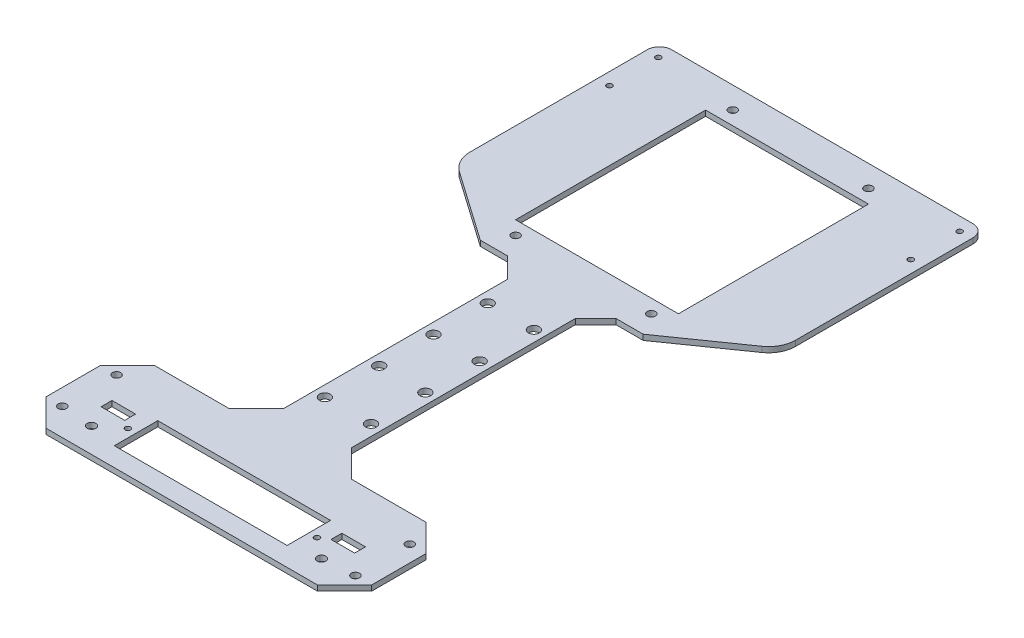
SolidWorks part; units mm, degrees
material "Acrílico (médio-alto impacto)"
ref_plane "Plano frontal" through (0, 0, 0) normal (0, 0, 1) x (1, 0, 0)
ref_plane "Plano superior" through (0, 0, 0) normal (0, 1, 0) x (1, 0, 0)
ref_plane "Plano direito" through (0, 0, 0) normal (1, 0, 0) x (0, 0, -1)
sketch "Esboço1" plane through (0, 0, 0) normal (0, 1, 0) x (1, 0, 0)
  line L0 (-18.0889, 17.9415) -> (-18.0889, 19.4415)
  line L1 (-13.5889, 23.9415) -> (97.4111, 23.9415)
  line L2 (-18.0889, 17.9415) -> (-18.0889, -45.8529)
  line L3 (-13.8247, -54.0444) -> (11.9111, -72.0648)
  line L4 (11.9111, -72.0648) -> (21.9111, -72.0648)
  line L5 (41.9111, -1077.9191) -> (41.9111, -72.0648) construction
  line L7 (97.6469, -54.0444) -> (71.9111, -72.0648)
  line L9 (101.9111, 17.9415) -> (101.9111, -45.8529)
  line L10 (101.9111, 17.9415) -> (101.9111, 19.4415)
  line L11 (21.9111, -72.0648) -> (29.4111, -79.5648)
  line L12 (29.4111, -79.5648) -> (29.4111, -162.0648)
  line L13 (29.4111, -162.0648) -> (19.4111, -172.0648)
  line L14 (19.4111, -172.0648) -> (-8.0889, -172.0648)
  line L15 (-18.0889, -182.0648) -> (-18.0889, -202.0648)
  line L16 (-8.0889, -212.0648) -> (91.9111, -212.0648)
  line L17 (-18.0889, -202.0648) -> (-8.0889, -212.0648)
  line L18 (-8.0889, -172.0648) -> (-18.0889, -182.0648)
  line L19 (71.9111, -72.0648) -> (61.9111, -72.0648)
  line L20 (41.9111, 23.9415) -> (41.9111, 1029.7958) construction
  line L21 (61.9111, -72.0648) -> (54.4111, -79.5648)
  line L22 (91.9111, -172.0648) -> (101.9111, -182.0648)
  line L23 (101.9111, -202.0648) -> (91.9111, -212.0648)
  line L24 (101.9111, -182.0648) -> (101.9111, -202.0648)
  line L25 (64.4111, -172.0648) -> (91.9111, -172.0648)
  line L26 (54.4111, -162.0648) -> (64.4111, -172.0648)
  line L27 (54.4111, -79.5648) -> (54.4111, -162.0648)
  arc A0 (-13.5889, 23.9415) -> (-18.0889, 19.4415) centre (-13.5889, 19.4415) ccw
  arc A1 (97.4111, 23.9415) -> (101.9111, 19.4415) centre (97.4111, 19.4415) cw
  arc A2 (97.6469, -54.0444) -> (101.9111, -45.8529) centre (91.9111, -45.8529) ccw
  arc A3 (-18.0889, -45.8529) -> (-13.8247, -54.0444) centre (-8.0889, -45.8529) ccw
  point P10 (101.9111, -51.0585)
  point P18 (-18.0889, -51.0585)
  point P20 (41.9111, -72.0648)
  point P22 (41.9111, 23.9415)
  point P26 (-18.0889, -212.0648)
  point P28 (-18.0889, -172.0648)
  point P37 (41.9111, -212.0648)
  point P43 (101.9111, -172.0648)
  point P44 (101.9111, -212.0648)
  dimension "D5" = 10
  dimension "D1" = 75
  dimension "D2" = 125
  dimension "D3" = 30
  dimension "D4" = 45
  dimension "D6" = 120
  dimension "D7" = 25
  dimension "D8" = 90
  dimension "D9" = 45
  dimension "D10" = 10
  dimension "D11" = 180
  dimension "D12" = 40
extrude "Base " add sketch "Esboço1" along normal blind 2 contours L9 A2 L7 L19 L21 L27 L26 L25 L22 L24 L23 L16 L17 L15 L18 L14 L13 L12 L11 L4 L3 A3 L2 L0 A0 L1 A1 L10
sketch "Esboço2" plane through (0, 2, 0) normal (0, 1, 0) x (1, 0, 0)
  line L0 (-13.5889, 23.9415) -> (97.4111, 23.9415) construction
  line L1 (-18.0889, -45.8529) -> (-18.0889, 19.4415) construction
  line L2 (41.9111, 23.9415) -> (41.9111, -27.3922) construction
  circle A0 centre (-13.5889, 19.0215) radius 1
  circle A1 centre (-13.5889, 1.0215) radius 1
  circle A2 centre (97.4111, 1.0215) radius 1
  circle A3 centre (97.4111, 19.0215) radius 1
  dimension "D1" = 4.92
  dimension "D2" = 4.5
  dimension "D3" = 2
  dimension "D4" = 2
  dimension "D5" = 4.5
  dimension "D6" = 18
extrude "Furo Bracket Motor" cut sketch "Esboço2" against normal blind 3
sketch "Esboço4" plane through (0, 0, 0) normal (0, -1, 0) x (1, 0, 0)
  line L1 (11.9111, 59.0635) -> (71.9111, 59.0635)
  line L2 (11.9111, 59.0635) -> (11.9111, -10.9365)
  line L3 (11.9111, -10.9365) -> (71.9111, -10.9365)
  line L4 (71.9111, 59.0635) -> (71.9111, -10.9365)
  line L5 (101.9111, -19.4415) -> (101.9111, 45.8529) construction
  line L7 (-13.5889, -23.9415) -> (97.4111, -23.9415) construction
  line L8 (-18.0889, -19.4415) -> (-18.0889, 45.8529) construction
  dimension "D1" = 60
  dimension "D2" = 70
  dimension "D3" = 30
  dimension "D4" = 13.005
  dimension "D5" = 30
extrude "Encaixe PCB" cut sketch "Esboço4" against normal through all
sketch "Esboço6" plane through (0, 0, 0) normal (0, -1, 0) x (1, 0, 0)
  line L0 (71.9111, 59.0635) -> (11.9111, 59.0635) construction
  line L1 (11.9111, 59.0635) -> (11.9111, -10.9365) construction
  line L2 (71.9111, -10.9365) -> (71.9111, 59.0635) construction
  line L3 (11.9111, -10.9365) -> (71.9111, -10.9365) construction
  circle A0 centre (16.9111, 64.0635) radius 1.5
  circle A1 centre (66.9111, 64.0635) radius 1.5
  circle A2 centre (66.9111, -15.9365) radius 1.5
  circle A3 centre (16.9111, -15.9365) radius 1.5
  dimension "D1" = 5
  dimension "D2" = 5
  dimension "D3" = 5
  dimension "D4" = 5
  dimension "D5" = 5
  dimension "D6" = 5
  dimension "D7" = 5
  dimension "D8" = 5
  dimension "D9" = 3
  dimension "D10" = 3
  dimension "D11" = 3
  dimension "D12" = 3
extrude "Parafuso PCB" cut sketch "Esboço6" against normal through all
sketch "Esboço7" plane through (0, 0, 0) normal (0, -1, 0) x (1, 0, 0)
  line L0 (29.4111, 79.5648) -> (29.4111, 162.0648) construction
  line L1 (41.9111, 212.0648) -> (41.9111, -23.9415) construction
  circle A0 centre (33.4111, 90.8148) radius 2
  circle A1 centre (33.4111, 110.8148) radius 2
  circle A2 centre (33.4111, 130.8148) radius 2
  circle A3 centre (33.4111, 150.8148) radius 2
  circle A4 centre (50.4111, 150.8148) radius 2
  circle A5 centre (50.4111, 130.8148) radius 2
  circle A6 centre (50.4111, 110.8148) radius 2
  circle A7 centre (50.4111, 90.8148) radius 2
  dimension "D1" = 11.25
  dimension "D2" = 20
  dimension "D3" = 20
  dimension "D4" = 20
  dimension "D5" = 11.25
  dimension "D6" = 4
  dimension "D7" = 4
  dimension "D8" = 4
  dimension "D9" = 4
  dimension "D10" = 4
  dimension "D11" = 4
extrude "Enforca Gato" cut sketch "Esboço7" against normal through all
sketch "Esboço8" plane through (0, 0, 0) normal (0, -1, 0) x (1, 0, 0)
  line L0 (41.9111, 212.0648) -> (41.9111, 196.2813) construction
  circle A0 centre (95.9111, 182.0648) radius 1.5
  circle A1 centre (95.9111, 202.0648) radius 1.5
  circle A2 centre (-12.0889, 202.0648) radius 1.5
  circle A3 centre (-12.0889, 182.0648) radius 1.5
  dimension "D1" = 10
  dimension "D2" = 6
  dimension "D3" = 3
  dimension "D4" = 10
  dimension "D5" = 6
  dimension "D6" = 3
extrude "Parafuso Apoio" cut sketch "Esboço8" against normal blind 10
sketch "Esboço9" plane through (0, 2, 0) normal (0, 1, 0) x (1, 0, 0)
  line L0 (41.9111, -212.0648) -> (41.9111, -165.8319) construction
  line L1 (-18.0889, -182.0648) -> (-18.0889, -202.0648) construction
  line L2 (101.9111, -182.0648) -> (101.9111, -202.0648) construction
  line L3 (-8.0889, -212.0648) -> (91.9111, -212.0648) construction
  line L4 (19.4111, -172.0648) -> (-8.0889, -172.0648) construction
  line L5 (73.7311, -205.0648) -> (10.0911, -205.0648)
  line L6 (73.7311, -205.0648) -> (73.7311, -189.0648)
  line L7 (73.7311, -189.0648) -> (10.0911, -189.0648)
  line L8 (10.0911, -205.0648) -> (10.0911, -189.0648)
  line L9 (3.9111, -195.0648) -> (-4.7889, -195.0648)
  line L10 (3.9111, -195.0648) -> (3.9111, -191.0648)
  line L11 (3.9111, -191.0648) -> (-4.7889, -191.0648)
  line L12 (-4.7889, -195.0648) -> (-4.7889, -191.0648)
  line L13 (88.6111, -195.0648) -> (88.6111, -191.0648)
  line L14 (79.9111, -191.0648) -> (88.6111, -191.0648)
  line L15 (79.9111, -195.0648) -> (79.9111, -191.0648)
  line L16 (79.9111, -195.0648) -> (88.6111, -195.0648)
  circle A0 centre (76.7311, -197.0648) radius 1
  circle A1 centre (7.0911, -197.0648) radius 1
  circle A2 centre (-0.4389, -202.9248) radius 1.6
  circle A3 centre (84.2611, -202.9248) radius 1.6
  dimension "D1" = 69.64
  dimension "D2" = 25.18
  dimension "D3" = 25.18
  dimension "D4" = 15
  dimension "D5" = 15
  dimension "D6" = 2
  dimension "D7" = 2
  dimension "D12" = 7.86
  dimension "D13" = 4.35
  dimension "D17" = 3.2
  dimension "D8" = 7
  dimension "D9" = 3
  dimension "D10" = 3
  dimension "D11" = 16
  dimension "D14" = 4.35
  dimension "D15" = 8.7
  dimension "D16" = 4
  dimension "D18" = 13.3
  dimension "D19" = 19
extrude "Corte-extrusão1" cut sketch "Esboço9" against normal blind 10
